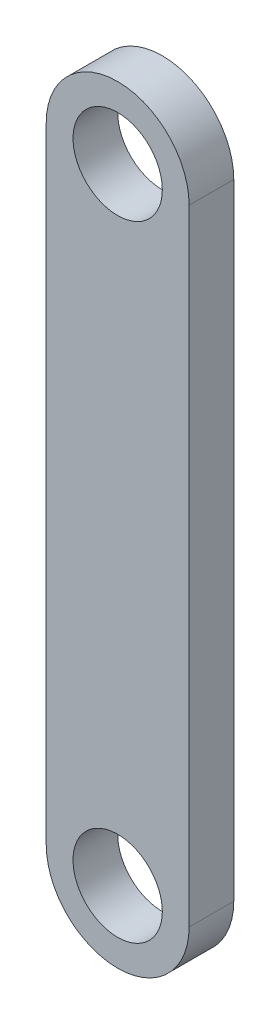
SolidWorks part; units mm, degrees
ref_plane "前基準面" through (0, 0, 0) normal (0, 0, 1) x (1, 0, 0)
ref_plane "上基準面" through (0, 0, 0) normal (0, 1, 0) x (1, 0, 0)
ref_plane "右基準面" through (0, 0, 0) normal (1, 0, 0) x (0, 0, -1)
sketch "草圖1" plane through (0, 0, 0) normal (0, 0, 1) x (1, 0, 0)
  line L0 (0, -3.5) -> (0, 3.5) construction
  line L1 (-0.8, -3.5) -> (-0.8, 3.5)
  line L2 (0.8, -3.5) -> (0.8, 3.5)
  arc A0 (-0.8, -3.5) -> (0.8, -3.5) centre (0, -3.5) ccw
  arc A1 (0.8, 3.5) -> (-0.8, 3.5) centre (0, 3.5) ccw
  circle A2 centre (0, 3.5) radius 0.5
  circle A3 centre (0, -3.5) radius 0.5
  point P2 (0, 0)
  dimension "D1" = 1
  dimension "D2" = 0.8
  dimension "D4" = 1
  dimension "D3" = 7
extrude "填料-伸長1" add sketch "草圖1" along normal blind 0.5
